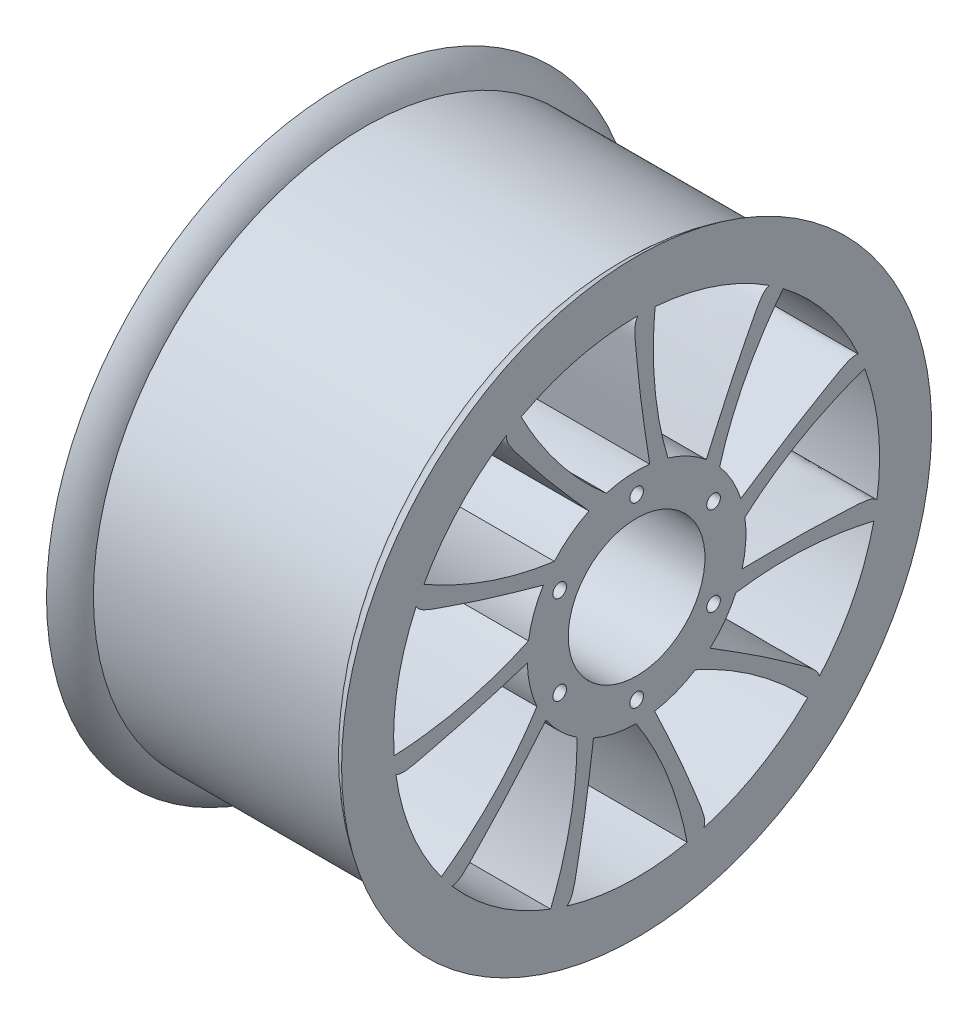
SolidWorks part; units mm, degrees
ref_plane "Front Plane" through (0, 0, 0) normal (0, 0, 1) x (1, 0, 0)
ref_plane "Top Plane" through (0, 0, 0) normal (0, 1, 0) x (1, 0, 0)
ref_plane "Right Plane" through (0, 0, 0) normal (1, 0, 0) x (0, 0, -1)
sketch "Sketch1" plane through (0, 0, 0) normal (0, 0, 1) x (1, 0, 0)
  line L0 (0, 0) -> (-332.4175, 0) construction
  line L1 (0, 0) -> (380.3952, 0)
  line L9 (-89.9583, 177.8) -> (89.9583, 177.8)
  line L10 (-91.3898, 198.1571) -> (91.3898, 198.1571)
  line L11 (-107.95, 215.9) -> (107.95, 215.9)
  line L12 (-107.95, 215.9) -> (-107.95, 177.8)
  line L13 (-107.95, 177.8) -> (-89.9583, 177.8)
  line L14 (107.95, 215.9) -> (107.95, 177.8)
  line L15 (107.95, 177.8) -> (89.9583, 177.8)
  spline S0 degree 2 poles (-107.95, 215.9) (-85.1422, 202.464) (-89.9583, 177.8) knots 0 0 0 1 1 1
  spline S1 degree 2 poles (107.95, 215.9) (85.1422, 202.464) (89.9583, 177.8) knots 0 0 0 1 1 1
  dimension "D1" = 215.9
sketch "Sketch3" plane through (0, 0, 0) normal (0, 0, 1) x (1, 0, 0)
revolve "Revolve2" add sketch "Sketch1" angle 360 about L1
sketch "Sketch4" plane through (-107.95, 0, 0) normal (-1, 0, 0) x (0, 0, 1)
  circle A0 centre (0, 0) radius 50
  point P3 (-504.1687, -73.1453)
  dimension "D1" = 100
extrude "Extrude-Thin3" add sketch "Sketch4" against normal through all separate body thin
sketch "Sketch5" plane through (-107.95, 0, 0) normal (-1, 0, 0) x (0, 0, 1)
  spline S0 degree 3 poles (84.4666, 156.4552) (103.2658, 154.156) (86.5631, 133.6982) (61.8158, 101.7044) (37.1555, 74.7157) (20.9629, 56.2188) knots 0 0 0 0 0.242506 0.417673 1 1 1 1
  spline S1 degree 2 poles (0, 60) (11.0038, 59.9324) (20.9629, 56.2188) knots 0 0 0 0.886411 0.886411 0.886411
  spline S2 degree 2 poles (0, 60) (53.3388, 96.1874) (84.4666, 156.4552) knots 0 0 0 1 1 1
  spline S3 degree 3 poles (155.6439, 85.9524) (170.2157, 73.8546) (145.1042, 65.6746) (106.9883, 52.1391) (71.6516, 42.767) (48.0293, 35.9608) knots 0 0 0 0 0.242506 0.417673 1 1 1 1
  spline S4 degree 3 poles (155.6439, 85.9524) (170.2157, 73.8546) (145.1042, 65.6746) (106.9883, 52.1391) (71.6516, 42.767) (48.0293, 35.9608) knots 0 0 0 0 0.242506 0.417673 1 1 1 1
  spline S5 degree 2 poles (32.4384, 50.4752) (41.6589, 44.4692) (48.0293, 35.9608) knots 0 0 0 0.886411 0.886411 0.886411
  spline S6 degree 2 poles (32.4384, 50.4752) (96.8743, 52.0809) (155.6439, 85.9524) knots 0 0 0 1 1 1
  spline S7 degree 3 poles (177.4054, -11.8397) (183.1234, -29.8951) (157.5758, -23.2003) (118.1928, -13.9801) (83.3988, -2.7599) (59.8468, 4.2856) knots 0 0 0 0 0.242506 0.417673 1 1 1 1
  spline S8 degree 2 poles (54.5779, 24.9249) (59.0876, 14.8874) (59.8468, 4.2856) knots 0 0 0 0.886411 0.886411 0.886411
  spline S9 degree 2 poles (54.5779, 24.9249) (109.6529, -8.5609) (177.4054, -11.8397) knots 0 0 0 1 1 1
  spline S10 degree 3 poles (142.8419, -105.8728) (137.8907, -124.1533) (120.0182, -104.7092) (91.8719, -75.6606) (68.6674, -47.4105) (52.6632, -28.7503) knots 0 0 0 0 0.242506 0.417673 1 1 1 1
  spline S11 degree 2 poles (59.3893, -8.5389) (57.7564, -19.4211) (52.6632, -28.7503) knots 0 0 0 0.886411 0.886411 0.886411
  spline S12 degree 2 poles (59.3893, -8.5389) (87.6175, -66.4848) (142.8419, -105.8728) knots 0 0 0 1 1 1
  spline S13 degree 3 poles (62.9271, -166.292) (48.8786, -178.9938) (44.3556, -152.9737) (36.3823, -113.3195) (32.1346, -77.0087) (28.7595, -52.6582) knots 0 0 0 0 0.242506 0.417673 1 1 1 1
  spline S14 degree 2 poles (45.345, -39.2916) (38.0879, -47.5635) (28.7595, -52.6582) knots 0 0 0 0.886411 0.886411 0.886411
  spline S15 degree 2 poles (45.345, -39.2916) (37.7641, -103.3001) (62.9271, -166.292) knots 0 0 0 1 1 1
  spline S16 degree 3 poles (-36.9666, -173.9147) (-55.652, -177.0049) (-45.3895, -152.6701) (-30.6583, -115.0002) (-14.6006, -82.1571) (-4.2751, -59.8475) knots 0 0 0 0 0.242506 0.417673 1 1 1 1
  spline S17 degree 2 poles (16.904, -57.5696) (6.3268, -60.6048) (-4.2751, -59.8475) knots 0 0 0 0.886411 0.886411 0.886411
  spline S18 degree 2 poles (16.904, -57.5696) (-24.079, -107.3184) (-36.9666, -173.9147) knots 0 0 0 1 1 1
  spline S19 degree 3 poles (-125.1236, -126.3207) (-142.5135, -118.8183) (-120.7238, -103.8949) (-87.9652, -80.1691) (-56.7003, -61.2212) (-35.9525, -48.0356) knots 0 0 0 0 0.242506 0.417673 1 1 1 1
  spline S20 degree 2 poles (-16.904, -57.5696) (-27.443, -54.4046) (-35.9525, -48.0356) knots 0 0 0 0.886411 0.886411 0.886411
  spline S21 degree 2 poles (-16.904, -57.5696) (-78.2773, -77.2639) (-125.1236, -126.3207) knots 0 0 0 1 1 1
  spline S22 degree 3 poles (-173.5548, -38.6208) (-184.128, -22.9076) (-157.7291, -22.1337) (-117.3438, -19.885) (-80.7981, -20.8481) (-56.2152, -20.9728) knots 0 0 0 0 0.242506 0.417673 1 1 1 1
  spline S23 degree 2 poles (-45.345, -39.2916) (-52.4998, -30.9312) (-56.2152, -20.9728) knots 0 0 0 0.886411 0.886411 0.886411
  spline S24 degree 2 poles (-45.345, -39.2916) (-107.6231, -22.6786) (-173.5548, -38.6208) knots 0 0 0 1 1 1
  spline S25 degree 3 poles (-166.8836, 61.341) (-167.2832, 80.276) (-144.6566, 66.6547) (-109.4665, 46.7125) (-79.243, 26.1442) (-58.6299, 12.7488) knots 0 0 0 0 0.242506 0.417673 1 1 1 1
  spline S26 degree 2 poles (-59.3893, -8.5389) (-60.8884, 2.3626) (-58.6299, 12.7488) knots 0 0 0 0.886411 0.886411 0.886411
  spline S27 degree 2 poles (-59.3893, -8.5389) (-102.7993, 39.107) (-166.8836, 61.341) knots 0 0 0 1 1 1
  spline S28 degree 3 poles (-107.228, 141.8274) (-97.3271, 157.9726) (-85.6566, 134.2808) (-66.8344, 98.4791) (-52.5288, 64.8359) (-42.4301, 42.4227) knots 0 0 0 0 0.242506 0.417673 1 1 1 1
  spline S29 degree 2 poles (-54.5779, 24.9249) (-49.9453, 34.9062) (-42.4301, 42.4227) knots 0 0 0 0.886411 0.886411 0.886411
  spline S30 degree 2 poles (-54.5779, 24.9249) (-65.3374, 88.4763) (-107.228, 141.8274) knots 0 0 0 1 1 1
  spline S31 degree 3 poles (-13.5282, 177.2846) (3.5297, 185.514) (0.5388, 159.2736) (-2.9828, 118.9793) (-9.1371, 82.9426) (-12.759, 58.6277) knots 0 0 0 0 0.242506 0.417673 1 1 1 1
  spline S32 degree 2 poles (-32.4384, 50.4752) (-23.1449, 56.3674) (-12.759, 58.6277) knots 0 0 0 0.886411 0.886411 0.886411
  spline S33 degree 2 poles (-32.4384, 50.4752) (-7.1314, 109.7551) (-13.5282, 177.2846) knots 0 0 0 1 1 1
  spline S34 degree 2 poles (32.4384, 50.4752) (41.6589, 44.4692) (48.0293, 35.9608) knots 0 0 0 0.886411 0.886411 0.886411
  spline S35 degree 2 poles (32.4384, 50.4752) (96.8743, 52.0809) (155.6439, 85.9524) knots 0 0 0 1 1 1
  spline S36 degree 3 poles (177.4054, -11.8397) (183.1234, -29.8951) (157.5758, -23.2003) (118.1928, -13.9801) (83.3988, -2.7599) (59.8468, 4.2856) knots 0 0 0 0 0.242506 0.417673 1 1 1 1
  spline S37 degree 2 poles (54.5779, 24.9249) (59.0876, 14.8874) (59.8468, 4.2856) knots 0 0 0 0.886411 0.886411 0.886411
  spline S38 degree 2 poles (54.5779, 24.9249) (109.6529, -8.5609) (177.4054, -11.8397) knots 0 0 0 1 1 1
  spline S39 degree 3 poles (142.8419, -105.8728) (137.8907, -124.1533) (120.0182, -104.7092) (91.8719, -75.6606) (68.6674, -47.4105) (52.6632, -28.7503) knots 0 0 0 0 0.242506 0.417673 1 1 1 1
  spline S40 degree 2 poles (59.3893, -8.5389) (57.7564, -19.4211) (52.6632, -28.7503) knots 0 0 0 0.886411 0.886411 0.886411
  spline S41 degree 2 poles (59.3893, -8.5389) (87.6175, -66.4848) (142.8419, -105.8728) knots 0 0 0 1 1 1
  spline S42 degree 3 poles (62.9271, -166.292) (48.8786, -178.9938) (44.3556, -152.9737) (36.3823, -113.3195) (32.1346, -77.0087) (28.7595, -52.6582) knots 0 0 0 0 0.242506 0.417673 1 1 1 1
  spline S43 degree 2 poles (45.345, -39.2916) (38.0879, -47.5635) (28.7595, -52.6582) knots 0 0 0 0.886411 0.886411 0.886411
  spline S44 degree 2 poles (45.345, -39.2916) (37.7641, -103.3001) (62.9271, -166.292) knots 0 0 0 1 1 1
  spline S45 degree 3 poles (-36.9666, -173.9147) (-55.652, -177.0049) (-45.3895, -152.6701) (-30.6583, -115.0002) (-14.6006, -82.1571) (-4.2751, -59.8475) knots 0 0 0 0 0.242506 0.417673 1 1 1 1
  spline S46 degree 2 poles (16.904, -57.5696) (6.3268, -60.6048) (-4.2751, -59.8475) knots 0 0 0 0.886411 0.886411 0.886411
  spline S47 degree 2 poles (16.904, -57.5696) (-24.079, -107.3184) (-36.9666, -173.9147) knots 0 0 0 1 1 1
  spline S48 degree 3 poles (-125.1236, -126.3207) (-142.5135, -118.8183) (-120.7238, -103.8949) (-87.9652, -80.1691) (-56.7003, -61.2212) (-35.9525, -48.0356) knots 0 0 0 0 0.242506 0.417673 1 1 1 1
  spline S49 degree 2 poles (-16.904, -57.5696) (-27.443, -54.4046) (-35.9525, -48.0356) knots 0 0 0 0.886411 0.886411 0.886411
  spline S50 degree 2 poles (-16.904, -57.5696) (-78.2773, -77.2639) (-125.1236, -126.3207) knots 0 0 0 1 1 1
  spline S51 degree 3 poles (-173.5548, -38.6208) (-184.128, -22.9076) (-157.7291, -22.1337) (-117.3438, -19.885) (-80.7981, -20.8481) (-56.2152, -20.9728) knots 0 0 0 0 0.242506 0.417673 1 1 1 1
  spline S52 degree 2 poles (-45.345, -39.2916) (-52.4998, -30.9312) (-56.2152, -20.9728) knots 0 0 0 0.886411 0.886411 0.886411
  spline S53 degree 2 poles (-45.345, -39.2916) (-107.6231, -22.6786) (-173.5548, -38.6208) knots 0 0 0 1 1 1
  spline S54 degree 3 poles (-166.8836, 61.341) (-167.2832, 80.276) (-144.6566, 66.6547) (-109.4665, 46.7125) (-79.243, 26.1442) (-58.6299, 12.7488) knots 0 0 0 0 0.242506 0.417673 1 1 1 1
  spline S55 degree 2 poles (-59.3893, -8.5389) (-60.8884, 2.3626) (-58.6299, 12.7488) knots 0 0 0 0.886411 0.886411 0.886411
  spline S56 degree 2 poles (-59.3893, -8.5389) (-102.7993, 39.107) (-166.8836, 61.341) knots 0 0 0 1 1 1
  spline S57 degree 3 poles (-107.228, 141.8274) (-97.3271, 157.9726) (-85.6566, 134.2808) (-66.8344, 98.4791) (-52.5288, 64.8359) (-42.4301, 42.4227) knots 0 0 0 0 0.242506 0.417673 1 1 1 1
  spline S58 degree 2 poles (-54.5779, 24.9249) (-49.9453, 34.9062) (-42.4301, 42.4227) knots 0 0 0 0.886411 0.886411 0.886411
  spline S59 degree 2 poles (-54.5779, 24.9249) (-65.3374, 88.4763) (-107.228, 141.8274) knots 0 0 0 1 1 1
  point P95 (0, 0)
  point P163 (0, 0)
extrude "Boss-Extrude5" add sketch "Sketch5" against normal through all contours S28 S29 S30 | S25 S26 S27 | S22 S23 S24 | S1 S2 S0 | S31 S32 S33 | S3 S34 S35 | S7 S8 S9 | S10 S11 S12 | S42 S43 S44 | S45 S46 S47 | S48 S49 S50
sketch "Sketch7" plane through (-107.95, 0, 0) normal (-1, 0, 0) x (0, 0, 1)
  circle A2 centre (0, 65) radius 5
  circle A3 centre (56.2917, 32.5) radius 5
  circle A4 centre (56.2917, -32.5) radius 5
  circle A5 centre (0, -65) radius 5
  circle A6 centre (-56.2917, -32.5) radius 5
  circle A7 centre (-56.2917, 32.5) radius 5
  point P24 (0, 0)
  dimension "D1" = 6
extrude "Cut-Extrude1" cut sketch "Sketch7" against normal through all
